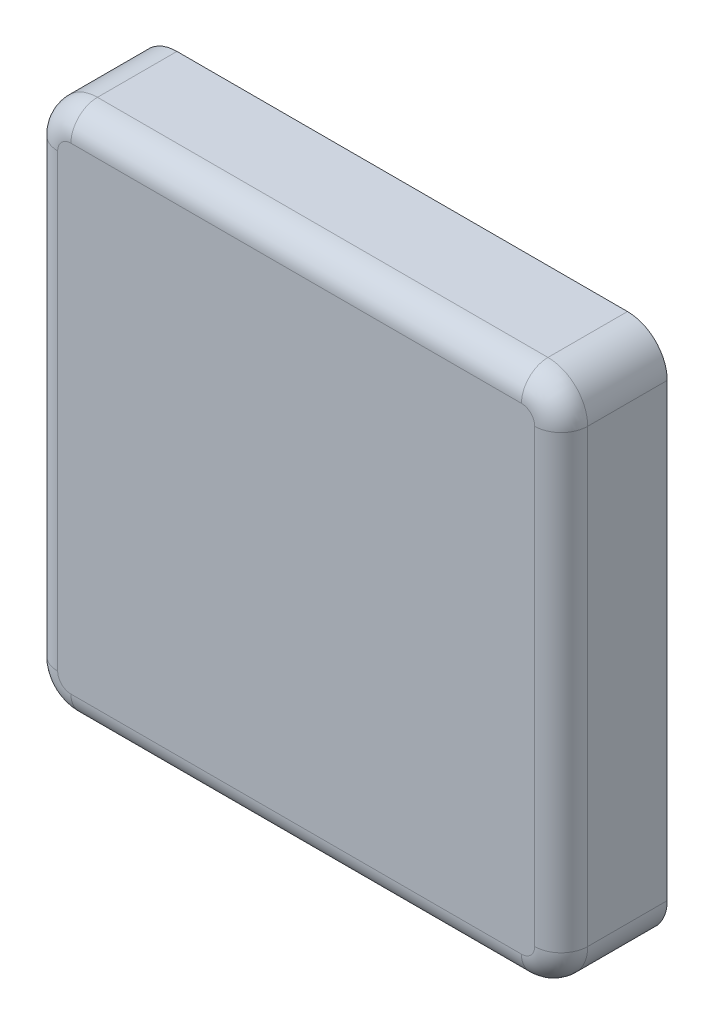
SolidWorks part; units mm, degrees
ref_plane "Front Plane" through (0, 0, 0) normal (0, 0, 1) x (1, 0, 0)
ref_plane "Top Plane" through (0, 0, 0) normal (0, 1, 0) x (1, 0, 0)
ref_plane "Right Plane" through (0, 0, 0) normal (1, 0, 0) x (0, 0, -1)
sketch "Sketch1" plane through (0, 0, 0) normal (0, 0, 1) x (1, 0, 0)
  line L1 (-1.6, -1.6) -> (1.6, -1.6)
  line L2 (-1.6, -1.6) -> (-1.6, 1.6)
  line L3 (-1.6, 1.6) -> (1.6, 1.6)
  line L4 (1.6, -1.6) -> (1.6, 1.6)
  line L5 (-1.6, -1.6) -> (1.6, 1.6) construction
  line L6 (-1.6, 1.6) -> (1.6, -1.6) construction
  circle A0 centre (0, 0) radius 4.5
  point P0 (0, 0)
  dimension "D3" = 9
  dimension "D1" = 3.2
  dimension "D2" = 3.2
extrude "Boss-Extrude1" add sketch "Sketch1" along normal blind 5.1
sketch "Sketch2" plane through (0, 0, 5.1) normal (0, 0, 1) x (1, 0, 0)
  line L1 (-8.5, -10) -> (8.5, -10)
  line L2 (-10, -8.5) -> (-10, 8.5)
  line L3 (-8.5, 10) -> (8.5, 10)
  line L4 (10, -8.5) -> (10, 8.5)
  line L5 (-10, -10) -> (10, 10) construction
  line L6 (-10, 10) -> (10, -10) construction
  arc A0 (8.5, -10) -> (10, -8.5) centre (8.5, -8.5) ccw
  arc A1 (-8.5, -10) -> (-10, -8.5) centre (-8.5, -8.5) cw
  arc A2 (-10, 8.5) -> (-8.5, 10) centre (-8.5, 8.5) cw
  arc A3 (8.5, 10) -> (10, 8.5) centre (8.5, 8.5) cw
  point P0 (0, 0)
  dimension "D3" = 1.5
  dimension "D1" = 20
  dimension "D2" = 20
extrude "Boss-Extrude2" add sketch "Sketch2" along normal blind 1
sketch "Sketch3" plane through (0, 0, 5.1) normal (0, 0, -1) x (-1, 0, 0)
  line L8 (8.5, 9) -> (-8.5, 9)
  line L9 (-9, 8.5) -> (-9, -8.5)
  line L10 (-8.5, -9) -> (8.5, -9)
  line L11 (9, -8.5) -> (9, 8.5)
  line L12 (-8.5, -10) -> (8.5, -10)
  line L13 (10, -8.5) -> (10, 8.5)
  line L14 (8.5, 10) -> (-8.5, 10)
  line L15 (-10, 8.5) -> (-10, -8.5)
  line L16 (-8.5, -10) -> (8.5, -10)
  line L17 (10, -8.5) -> (10, 8.5)
  line L18 (8.5, 10) -> (-8.5, 10)
  line L19 (-10, 8.5) -> (-10, -8.5)
  arc A8 (-8.5, 9) -> (-9, 8.5) centre (-8.5, 8.5) ccw
  arc A9 (-9, -8.5) -> (-8.5, -9) centre (-8.5, -8.5) ccw
  arc A10 (8.5, -9) -> (9, -8.5) centre (8.5, -8.5) ccw
  arc A11 (9, 8.5) -> (8.5, 9) centre (8.5, 8.5) ccw
  arc A12 (-10, -8.5) -> (-8.5, -10) centre (-8.5, -8.5) ccw
  arc A13 (8.5, -10) -> (10, -8.5) centre (8.5, -8.5) ccw
  arc A14 (10, 8.5) -> (8.5, 10) centre (8.5, 8.5) ccw
  arc A15 (-8.5, 10) -> (-10, 8.5) centre (-8.5, 8.5) ccw
  arc A16 (-10, -8.5) -> (-8.5, -10) centre (-8.5, -8.5) ccw
  arc A17 (8.5, -10) -> (10, -8.5) centre (8.5, -8.5) ccw
  arc A18 (10, 8.5) -> (8.5, 10) centre (8.5, 8.5) ccw
  arc A19 (-8.5, 10) -> (-10, 8.5) centre (-8.5, 8.5) ccw
  dimension "D1" = 0
  dimension "D2" = 1
extrude "Boss-Extrude3" add sketch "Sketch3" along normal blind 3
fillet "Fillet1" radius 1 8 edges at (0, -10, 6.1) (-9.5607, -9.5607, 6.1) (-10, 0, 6.1) (-9.5607, 9.5607, 6.1) (0, 10, 6.1) (9.5607, 9.5607, 6.1) (10, 0, 6.1) (9.5607, -9.5607, 6.1)
